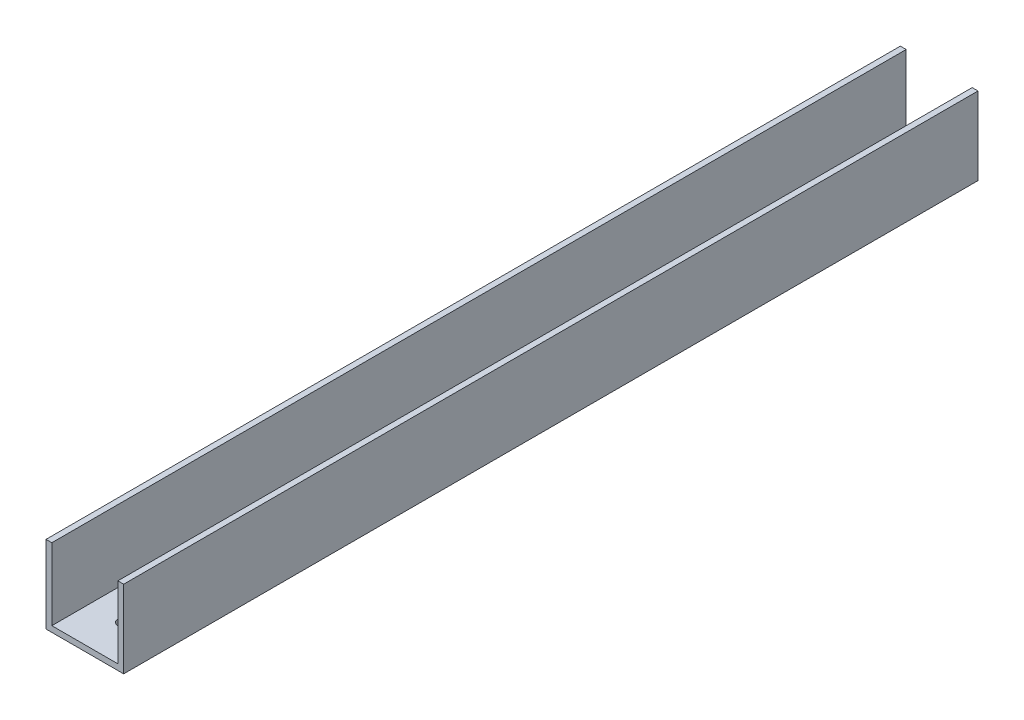
SolidWorks part; units mm, degrees
ref_plane "Plan de face" through (0, 0, 0) normal (0, 0, 1) x (1, 0, 0)
ref_plane "Plan de dessus" through (0, 0, 0) normal (0, 1, 0) x (1, 0, 0)
ref_plane "Plan de droite" through (0, 0, 0) normal (1, 0, 0) x (0, 0, -1)
sketch "Esquisse1" plane through (0, 0, 0) normal (0, 0, 1) x (1, 0, 0)
  line L0 (-25.8453, 11.3571) -> (-25.8453, -8.6429)
  line L1 (-25.8453, -8.6429) -> (-5.8453, -8.6429)
  line L2 (-5.8453, -8.6429) -> (-5.8453, 11.3571)
  line L3 (-5.8453, 11.3571) -> (-7.3453, 11.3571)
  line L4 (-7.3453, 11.3571) -> (-7.3453, -7.1429)
  line L5 (-7.3453, -7.1429) -> (-24.3453, -7.1429)
  line L6 (-24.3453, -7.1429) -> (-24.3453, 11.3571)
  line L7 (-24.3453, 11.3571) -> (-25.8453, 11.3571)
  dimension "D1" = 1.5
  dimension "D2" = 1.5
  dimension "D3" = 1.5
  dimension "D4" = 20
  dimension "D5" = 20
  dimension "D6" = 20
extrude "Extrusion1" add sketch "Esquisse1" along normal blind 220
sketch "Esquisse2" plane through (0, -8.6429, 0) normal (0, -1, 0) x (1, 0, 0)
  line L0 (-15.8453, 210) -> (-15.8453, 10) construction
  line L1 (-5.8453, 220) -> (-5.8453, 0) construction
  line L2 (-25.8453, 220) -> (-5.8453, 220) construction
  line L3 (-25.8453, 0) -> (-5.8453, 0) construction
  circle A0 centre (-15.8453, 210) radius 1.5
  circle A1 centre (-15.8453, 10) radius 1.5
  circle A2 centre (-15.8453, 160) radius 1.5
  circle A3 centre (-15.8453, 110) radius 1.5
  circle A4 centre (-15.8453, 60) radius 1.5
  point P7 (-15.8453, 0)
  dimension "D1" = 10
  dimension "D4" = 50
  dimension "D2" = 10
  dimension "D3" = 10
  dimension "D5" = 50
extrude "Extrusion2" cut sketch "Esquisse2" against normal blind 200
